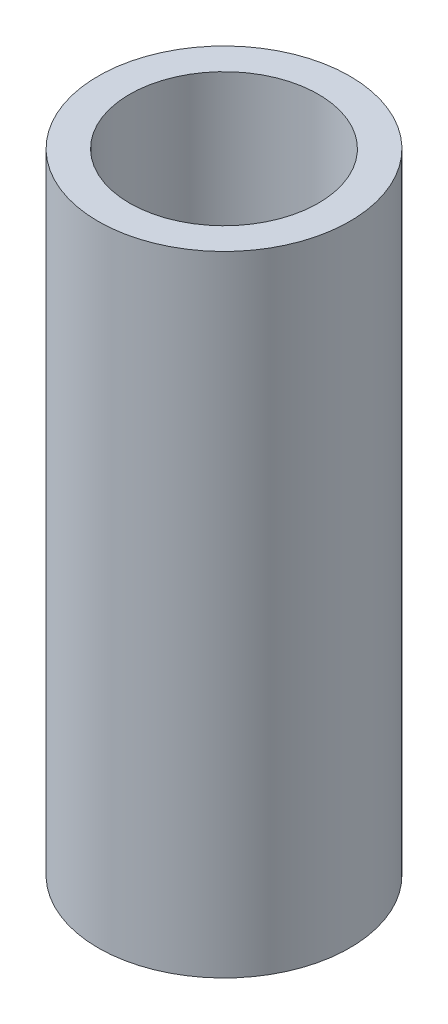
SolidWorks part; units mm, degrees
ref_plane "前视基准面" through (0, 0, 0) normal (0, 0, 1) x (1, 0, 0)
ref_plane "上视基准面" through (0, 0, 0) normal (0, 1, 0) x (1, 0, 0)
ref_plane "右视基准面" through (0, 0, 0) normal (1, 0, 0) x (0, 0, -1)
other "Configuration Table"
sketch "草图1" plane through (0, 0, 0) normal (0, 1, 0) x (1, 0, 0)
  circle A0 centre (0, 0) radius 1.5
  circle A1 centre (0, 0) radius 2
  dimension "D1" = 3
  dimension "D2" = 4
extrude "凸台-拉伸1" add sketch "草图1" along normal blind 10
